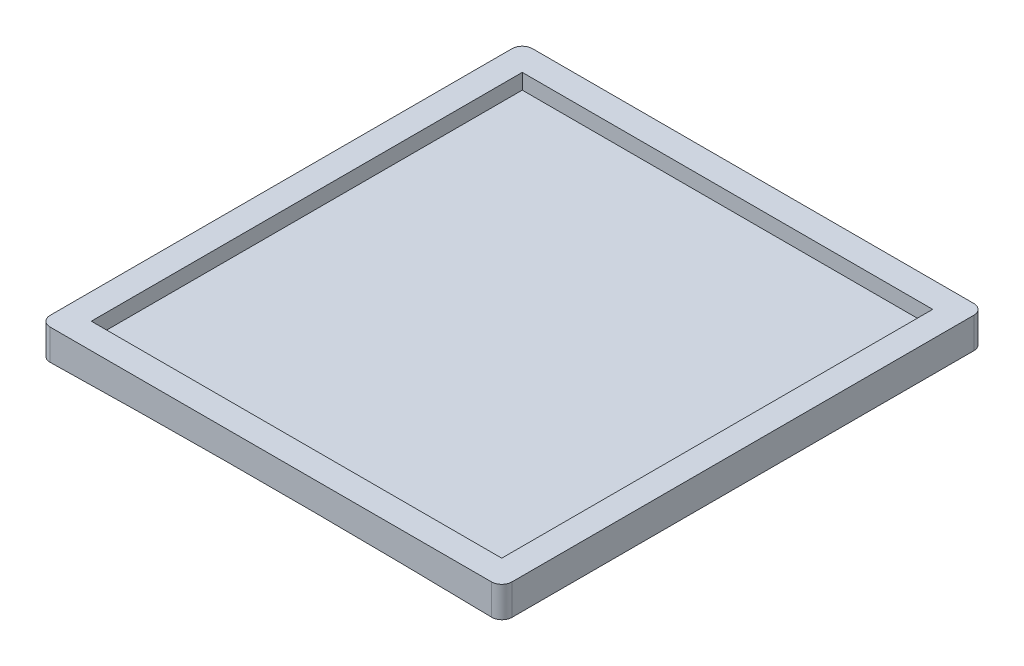
SolidWorks part; units mm, degrees
ref_plane "Front Plane" through (0, 0, 0) normal (0, 0, 1) x (1, 0, 0)
ref_plane "Top Plane" through (0, 0, 0) normal (0, 1, 0) x (1, 0, 0)
ref_plane "Right Plane" through (0, 0, 0) normal (1, 0, 0) x (0, 0, -1)
sketch "Sketch1" plane through (0, 0, 0) normal (0, 1, 0) x (1, 0, 0)
  line L0 (-21.5, -23.5) -> (21.5, -23.5) construction
  line L1 (21.5, 23.5) -> (-21.5, 23.5)
  line L2 (22.5, 22.5) -> (22.5, -22.5)
  line L3 (21.5, -23.5) -> (-21.5, -23.5)
  line L4 (-22.5, 22.5) -> (-22.5, -22.5)
  line L5 (22.5, 23.5) -> (-22.5, -23.5) construction
  line L6 (22.5, -23.5) -> (-22.5, 23.5) construction
  line L7 (-22.5, 4) -> (-22.5, -22.5) construction
  arc A0 (-21.5, 23.5) -> (-22.5, 22.5) centre (-21.5, 22.5) ccw
  arc A1 (21.5, 23.5) -> (22.5, 22.5) centre (21.5, 22.5) cw
  arc A2 (22.5, -22.5) -> (21.5, -23.5) centre (21.5, -22.5) cw
  arc A3 (-21.5, -23.5) -> (-22.5, -22.5) centre (-21.5, -22.5) cw
  point P0 (0, 0)
  dimension "D1" = 1
extrude "Boss-Extrude1" add sketch "Sketch1" against normal blind 3
sketch "Sketch2" plane through (0, 0, 0) normal (0, 0, 1) x (1, 0, 0)
  line L0 (-22.5, -3) -> (22.5, -3)
  arc A0 (-22.5, -3) -> (22.5, -3) centre (0, -1015.375) cw
  point P3 (0, -2.75)
  dimension "D1" = 2.75
extrude "Cut-Extrude1" cut sketch "Sketch2" against normal through all both and the other way through all
sketch "Sketch4" plane through (0, 0, 0) normal (0, 1, 0) x (1, 0, 0)
  line L1 (-20, -21) -> (20, -21)
  line L2 (-20, -21) -> (-20, 21)
  line L3 (-20, 21) -> (20, 21)
  line L4 (20, -21) -> (20, 21)
  line L5 (-20, -21) -> (20, 21) construction
  line L6 (-20, 21) -> (20, -21) construction
  point P0 (0, 0)
  dimension "D1" = 42
  dimension "D2" = 40
extrude "Cut-Extrude2" cut sketch "Sketch4" against normal blind 1.5
